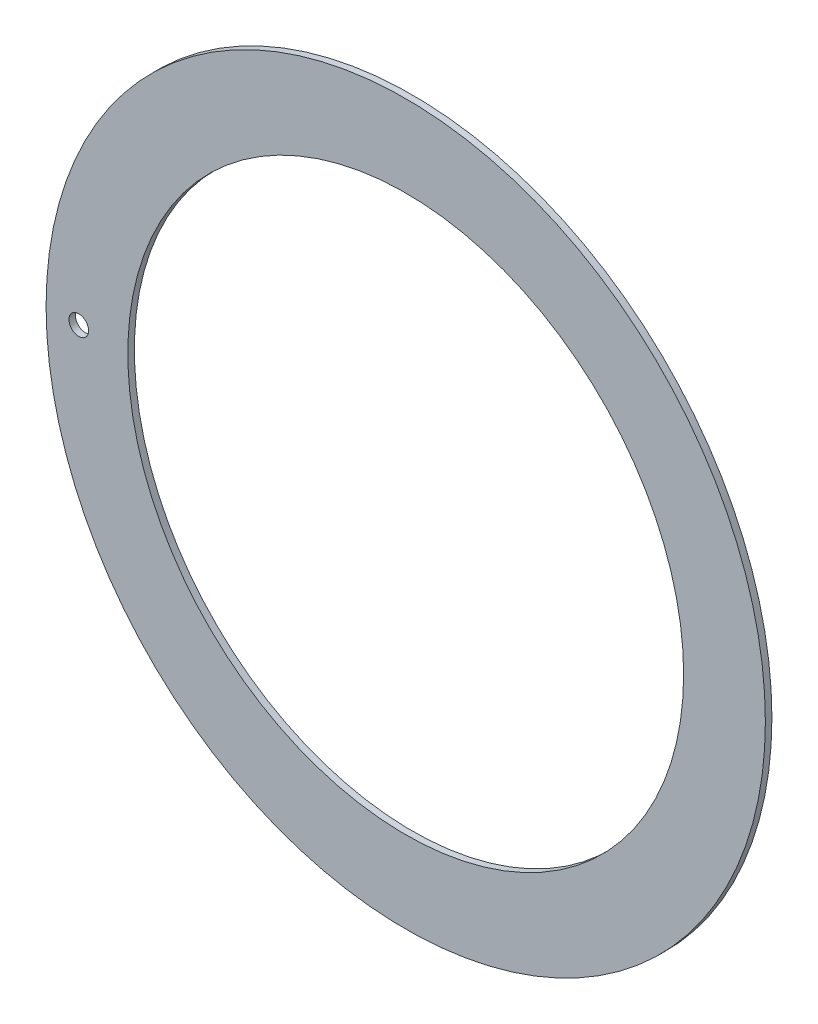
SolidWorks part; units mm, degrees
ref_plane "前视基准面" through (0, 0, 0) normal (0, 0, 1) x (1, 0, 0)
ref_plane "上视基准面" through (0, 0, 0) normal (0, 1, 0) x (1, 0, 0)
ref_plane "右视基准面" through (0, 0, 0) normal (1, 0, 0) x (0, 0, -1)
other "Configuration Table"
sketch "草图1" plane through (0, 0, 0) normal (0, 0, 1) x (1, 0, 0)
  line L0 (3830.0569, -111.3112) -> (3830.0569, 382.5434) construction
  circle A0 centre (3830.0569, 134.8848) radius 55
  circle A1 centre (3830.0569, 134.8848) radius 42.5
  circle A2 centre (3780.0569, 134.8848) radius 1.5
  point P5 (0, 0)
  point P6 (-228.7543, 174.7402)
  point P7 (-230.3123, 173.1074)
  point P8 (0, 0)
  point P11 (-230.8438, 173.7141)
  dimension "D1" = 110
  dimension "D2" = 85
  dimension "D4" = 3
  dimension "D3" = 50
extrude "凸台-拉伸1" add sketch "草图1" along normal blind 1
